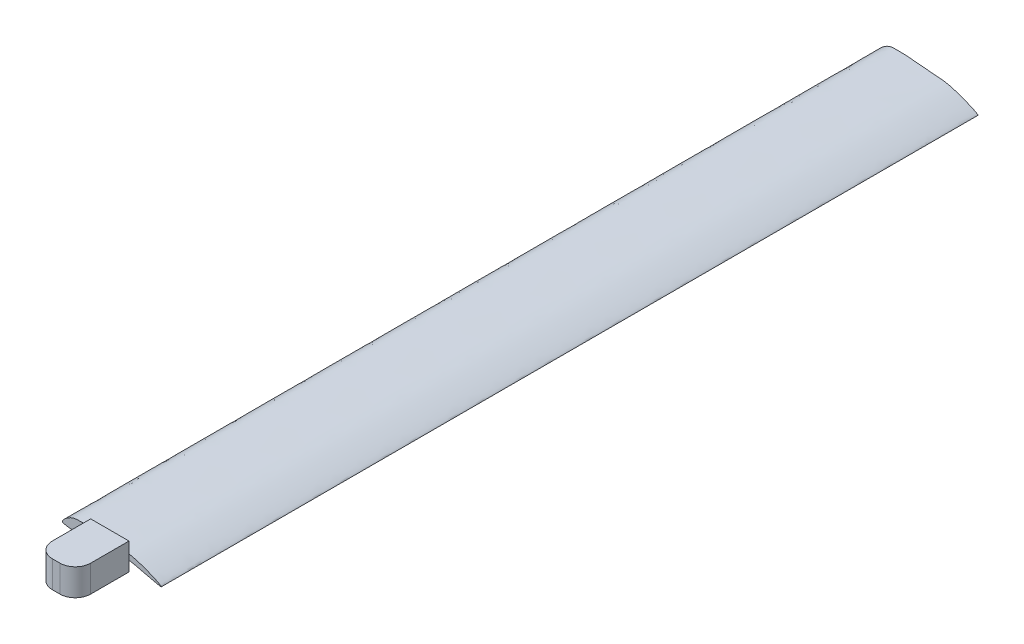
SolidWorks part; units mm, degrees
ref_plane "Front Plane" through (0, 0, 0) normal (0, 0, 1) x (1, 0, 0)
ref_plane "Top Plane" through (0, 0, 0) normal (0, 1, 0) x (1, 0, 0)
ref_plane "Right Plane" through (0, 0, 0) normal (1, 0, 0) x (0, 0, -1)
sketch "Sketch1" plane through (0, 0, 0) normal (0, 1, 0) x (1, 0, 0)
  line L1 (-20.3822, 26.672) -> (29.6178, 26.672)
  line L2 (-20.3822, 26.672) -> (-20.3822, -43.328)
  line L3 (-20.3822, -43.328) -> (29.6178, -43.328)
  line L4 (29.6178, 26.672) -> (29.6178, -43.328)
  dimension "D1" = 50
  dimension "D2" = 70
extrude "Boss-Extrude1" add sketch "Sketch1" along normal blind 35
fillet "Fillet1" radius 20 2 edges at (-20.3822, 17.5, 43.328) (29.6178, 17.5, 43.328)
sketch "Sketch2" plane through (0, 0, -26.672) normal (0, 0, -1) x (-1, 0, 0)
  line L0 (-4.6178, 35) -> (-4.6178, 0) construction
  line L1 (-29.6178, 35) -> (20.3822, 35) construction
  line L2 (-29.6178, 0) -> (20.3822, 0) construction
  line L4 (20.3822, 35) -> (20.3822, 0) construction
  line L5 (20.3822, 17.5) -> (-29.6178, 17.5) construction
  line L6 (-29.6178, 35) -> (-29.6178, 0) construction
  spline S0 degree 3 poles (45.1321, 9.5312) (60.3984, 13.4348) (47.219, 24.5865) (31.6879, 26.0491) (13.5797, 24.6113) (-11.3379, 21.7313) (-34.4835, 22.8207) (-92.5608, -3.1006) (-44.4007, 10.5427) (-26.5619, 14.1344) (-6.8565, 14.2364) (16.1777, 11.4297) (45.1321, 9.5312) (60.3984, 13.4348) (47.219, 24.5865) knots -0.265868 -0.145606 -0.014561 0 0.05477 0.091549 0.195016 0.25072 0.368624 0.511365 0.642931 0.680512 0.734132 0.854394 0.985439 1 1.05477 1.091549 1.195016 only from (56.7221, 12.9133) to (56.7221, 12.9133)
  point P6 (-8.6633, 27.2119)
  point P15 (6.114, 28.6419)
  point P17 (-40.7138, 16.4142)
  point P19 (-30.8621, 18.2203)
  point P21 (-16.5772, 18.6308)
  point P23 (0, 0)
  point P25 (14.0646, 16.2344)
extrude "Boss-Extrude2" add sketch "Sketch2" along normal blind 1065
